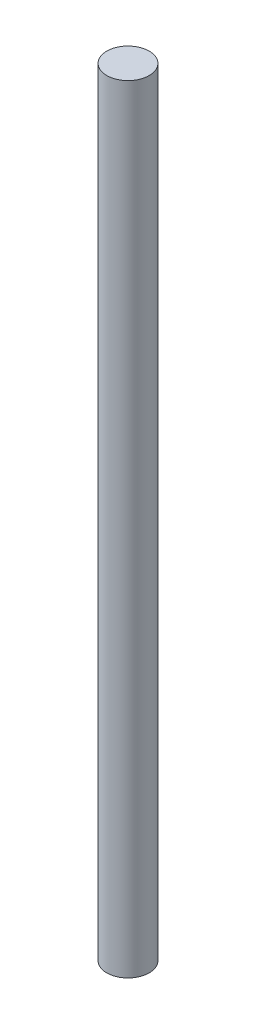
SolidWorks part; units mm, degrees
ref_plane "Front Plane" through (0, 0, 0) normal (0, 0, 1) x (1, 0, 0)
ref_plane "Top Plane" through (0, 0, 0) normal (0, 1, 0) x (1, 0, 0)
ref_plane "Right Plane" through (0, 0, 0) normal (1, 0, 0) x (0, 0, -1)
sketch "Sketch1" plane through (0, 0, 0) normal (0, 1, 0) x (1, 0, 0)
  circle A0 centre (0, 0) radius 1.5
  dimension "D1" = 3
extrude "Boss-Extrude1" add sketch "Sketch1" along normal blind 55
